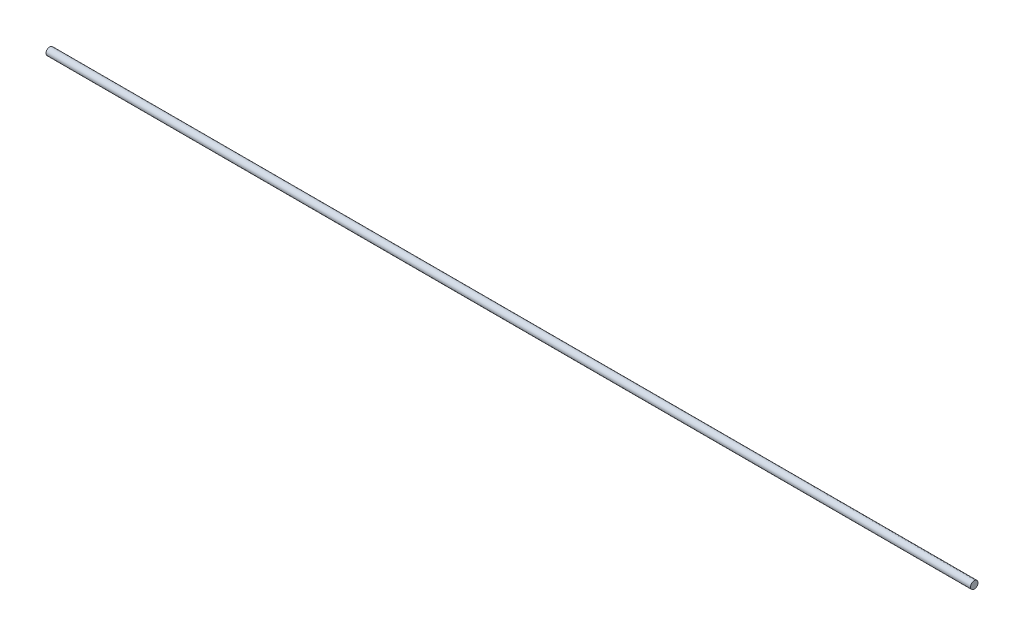
SolidWorks part; units mm, degrees
material "AISI 1020"
ref_plane "Front Plane" through (0, 0, 0) normal (0, 0, 1) x (1, 0, 0)
ref_plane "Top Plane" through (0, 0, 0) normal (0, 1, 0) x (1, 0, 0)
ref_plane "Right Plane" through (0, 0, 0) normal (1, 0, 0) x (0, 0, -1)
sketch "Sketch1" plane through (0, 0, 0) normal (0, 1, 0) x (1, 0, 0)
  line L0 (-590, 0) -> (590, 0)
  point P3 (0, 0)
  dimension "D1" = 1180
sweep "Sweep1" add path "Sketch1" circular profile diameter 9.525 parameters "D3"=9.525
sketch "Sketch2" plane through (0, 0, 0) normal (0, 1, 0) x (1, 0, 0)
  line L0 (-590, 4.7625) -> (-590, -4.7625) construction
  line L1 (0, -5.2388) -> (0, 5.2388) construction
  circle A0 centre (-590, 0) radius 4
  circle A1 centre (590, 0) radius 4
  dimension "D1" = 8
